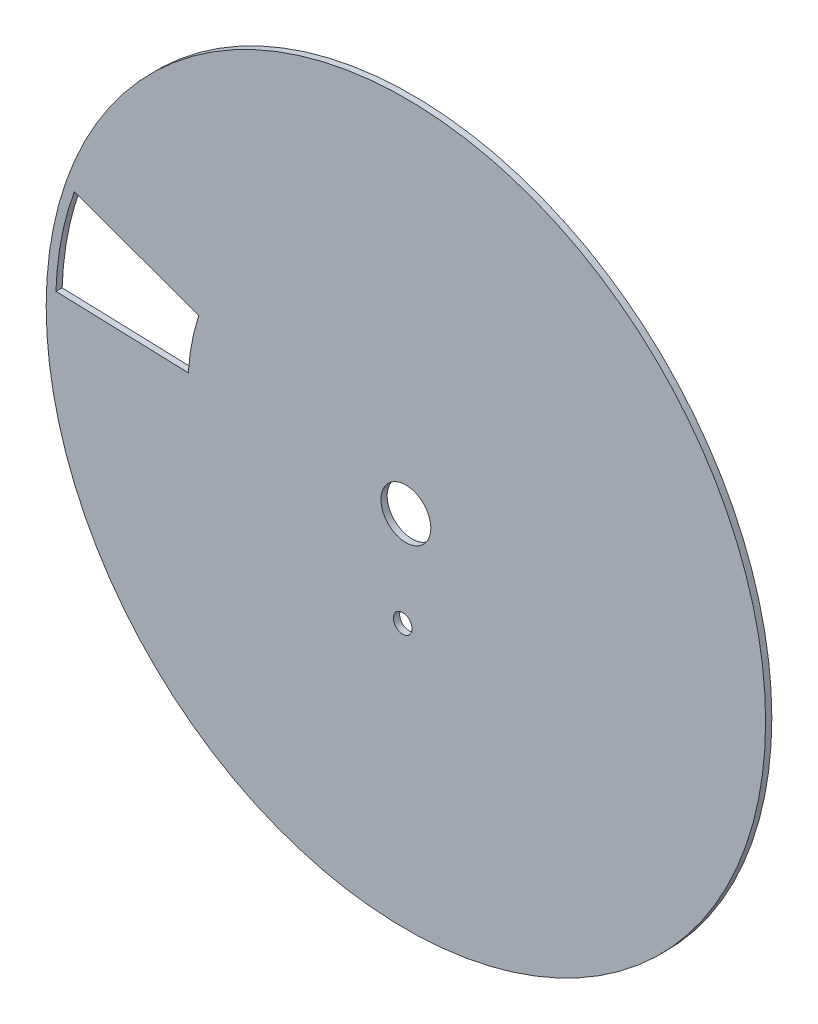
SolidWorks part; units mm, degrees
ref_plane "Plan de face" through (0, 0, 0) normal (0, 0, 1) x (1, 0, 0)
ref_plane "Plan de dessus" through (0, 0, 0) normal (0, 1, 0) x (1, 0, 0)
ref_plane "Plan de droite" through (0, 0, 0) normal (1, 0, 0) x (0, 0, -1)
sketch "Esquisse1" plane through (0, 0, 0) normal (0, 0, 1) x (1, 0, 0)
  circle A0 centre (0, 0) radius 57.75
  dimension "D1" = 115.5
extrude "Boss.-Extru.1" add sketch "Esquisse1" along normal blind 1
sketch "Esquisse2" plane through (0, 0, 1) normal (0, 0, 1) x (1, 0, 0)
  circle A0 centre (0, 0) radius 4
extrude "Enlèv. mat.-Extru.1" cut sketch "Esquisse2" against normal blind 10
sketch "Esquisse4" plane through (0, 0, 0) normal (0, 0, -1) x (-1, 0, 0)
  line L0 (33.2437, 10.9479) -> (53.2292, 18.1688)
  line L1 (54.8804, 18.7654) -> (33.2437, 10.9479) construction
  line L2 (34.9346, 2.1381) -> (56.1846, 2.8301)
  line L3 (34.9346, 2.1381) -> (57.9281, 2.8869) construction
  arc A0 (33.2437, 10.9479) -> (34.9346, 2.1381) centre (0, 0) cw
  arc A1 (53.2292, 18.1688) -> (56.1846, 2.8301) centre (6.3057, 1.1737) cw
  dimension "D1" = 21.25
  dimension "D2" = 21.25
extrude "Enlèv. mat.-Extru.4" cut sketch "Esquisse4" against normal blind 10
sketch "Esquisse5" plane through (0, 0, 0) normal (0, 0, -1) x (-1, 0, 0)
  line L0 (0, 0) -> (0.6509, -19.9894) construction
  arc A0 (-3.501, 19.6912) -> (2.2125, 19.8772) centre (0, 0) ccw construction
  circle A1 centre (0.5046, -15.4958) radius 1.5
extrude "Enlèv. mat.-Extru.5" cut sketch "Esquisse5" against normal blind 10
